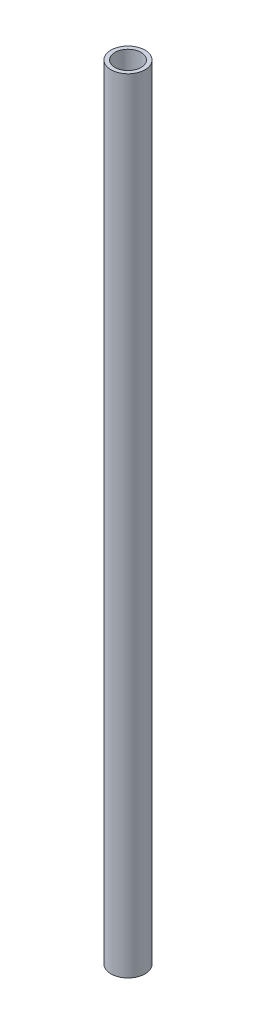
SolidWorks part; units mm, degrees
material "Alloy Steel"
ref_plane "Front Plane" through (0, 0, 0) normal (0, 0, 1) x (1, 0, 0)
ref_plane "Top Plane" through (0, 0, 0) normal (0, 1, 0) x (1, 0, 0)
ref_plane "Right Plane" through (0, 0, 0) normal (1, 0, 0) x (0, 0, -1)
sketch "Sketch1" plane through (0, 0, 0) normal (0, 1, 0) x (1, 0, 0)
  circle A0 centre (0, 0) radius 6.35
  circle A1 centre (0, 0) radius 4.8768
  dimension "D1" = 12.7
  dimension "D2" = 1.4732
extrude "Boss-Extrude1" add sketch "Sketch1" along normal mid plane 292.1
sketch "Sketch2" plane through (0, 0, 0) normal (0, 0, 1) x (1, 0, 0)
  line L0 (0, 185.9598) -> (0, -185.9598) construction
  dimension "D1" = 371.9195
